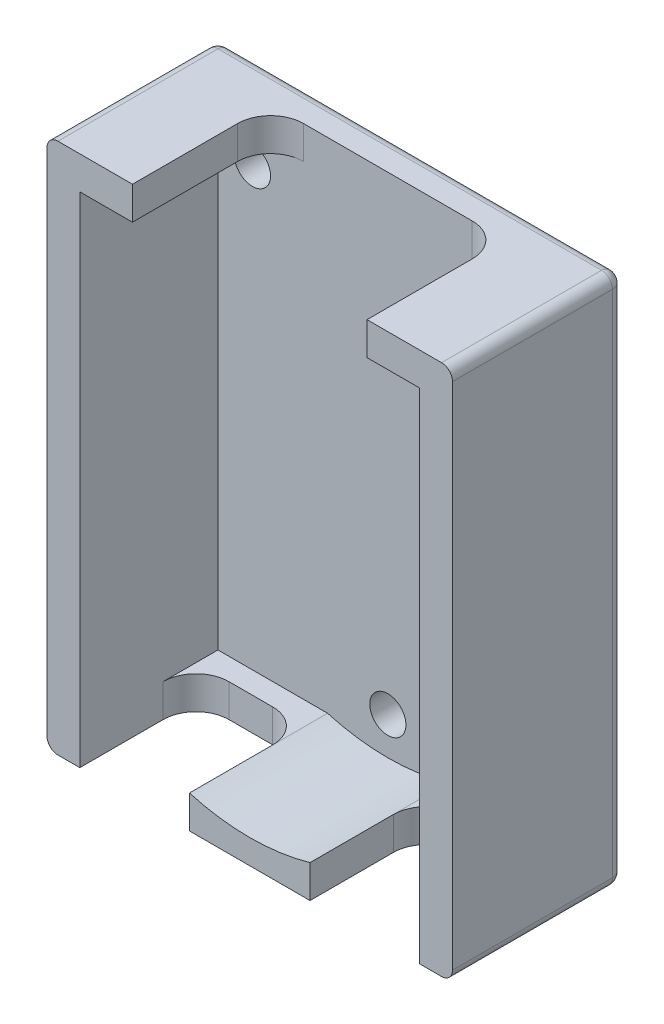
SolidWorks part; units mm, degrees
ref_plane "Front Plane" through (0, 0, 0) normal (0, 0, 1) x (1, 0, 0)
ref_plane "Top Plane" through (0, 0, 0) normal (0, 1, 0) x (1, 0, 0)
ref_plane "Right Plane" through (0, 0, 0) normal (1, 0, 0) x (0, 0, -1)
ref_plane "Plane1" through (0, 0, 0) normal (-0.7071, 0.7071, 0) x (0.7071, 0.7071, 0)
ref_plane "Plane2" through (0, 0, 0) normal (0.7071, 0.7071, 0) x (0.7071, -0.7071, 0)
sketch "Sketch1" plane through (0, 0, 0) normal (0, 0, 1) x (1, 0, 0)
  line L1 (-15.5, -21.25) -> (15.5, -21.25)
  line L2 (-15.5, -21.25) -> (-15.5, 21.25)
  line L3 (-15.5, 21.25) -> (15.5, 21.25)
  line L4 (15.5, -21.25) -> (15.5, 21.25)
  line L5 (-15.5, -21.25) -> (15.5, 21.25) construction
  line L6 (-15.5, 21.25) -> (15.5, -21.25) construction
  point P0 (0, 0)
  dimension "D1" = 31
  dimension "D2" = 42.5
extrude "Boss-Extrude1" add sketch "Sketch1" along normal blind 3
sketch "Sketch2" plane through (0, 0, 0) normal (0, 0, 1) x (1, 0, 0)
  line L0 (-18.5, -24.25) -> (-18.5, 24.25)
  line L1 (-15.5, -21.25) -> (15.5, -21.25)
  line L2 (-15.5, -21.25) -> (-15.5, 21.25)
  line L3 (-15.5, 21.25) -> (15.5, 21.25)
  line L4 (15.5, -21.25) -> (15.5, 21.25)
  line L5 (-15.5, -21.25) -> (15.5, 21.25) construction
  line L6 (-15.5, 21.25) -> (15.5, -21.25) construction
  line L7 (-18.5, 24.25) -> (18.5, 24.25)
  line L8 (18.5, -24.25) -> (18.5, 24.25)
  line L9 (-18.5, -24.25) -> (18.5, -24.25)
  line L10 (15.5, -21.25) -> (15.5, 21.25) construction
  line L11 (-15.5, -21.25) -> (15.5, -21.25) construction
  point P0 (0, 0)
  dimension "D1" = 3
extrude "Boss-Extrude2" add sketch "Sketch2" along normal blind 15.6
sketch "Sketch3" plane through (0, 0, 0) normal (0, 0, -1) x (-1, 0, 0)
  circle A0 centre (12.35, 18.6) radius 1.65
  circle A1 centre (0, -18.6) radius 1.65
  dimension "D1" = 3.3
  dimension "D2" = 12.35
  dimension "D3" = 18.6
  dimension "D4" = 18.6
extrude "Cut-Extrude1" cut sketch "Sketch3" against normal up to next
mirror "Mirror1" about plane through (0, 0, 0) normal (1, 0, 0) of "Cut-Extrude1"
sketch "Sketch4" plane through (0, 24.25, 0) normal (0, 1, 0) x (1, 0, 0)
  line L0 (18.5, -15.6) -> (-18.5, -15.6) construction
  line L1 (-10.7, -15.6) -> (10.7, -15.6)
  line L2 (-10.7, -15.6) -> (-10.7, -3)
  line L3 (-10.7, -3) -> (10.7, -3)
  line L4 (10.7, -15.6) -> (10.7, -3)
  line L5 (-10.7, -15.6) -> (10.7, -3) construction
  line L6 (-10.7, -3) -> (10.7, -15.6) construction
  line L8 (18.5, 0) -> (-18.5, 0) construction
  point P0 (0, -9.3)
  dimension "D1" = 3
extrude "Cut-Extrude2" cut sketch "Sketch4" against normal up to next
sketch "Sketch5" plane through (0, -24.25, 0) normal (0, -1, 0) x (1, 0, 0)
  line L0 (-18.5, 15.6) -> (18.5, 15.6) construction
  line L1 (15.5, 15.6) -> (5.5, 15.6)
  line L2 (15.5, 15.6) -> (15.5, 5)
  line L3 (15.5, 5) -> (5.5, 5)
  line L4 (5.5, 15.6) -> (5.5, 5)
  line L5 (15.5, 15.6) -> (5.5, 5) construction
  line L6 (15.5, 5) -> (5.5, 15.6) construction
  line L7 (-18.5, 0) -> (18.5, 0) construction
  line L8 (18.5, 15.6) -> (18.5, 0) construction
  line L9 (0, -1.65) -> (0, 1.65) construction
  point P0 (10.5, 10.3)
  dimension "D1" = 5
  dimension "D2" = 3
  dimension "D3" = 5.5
extrude "Cut-Extrude3" cut sketch "Sketch5" against normal up to next
mirror "Mirror2" about plane through (0, 0, 0) normal (1, 0, 0) of "Cut-Extrude3"
sketch "Sketch6" plane through (0, 0, 15.6) normal (0, 0, 1) x (1, 0, 0)
  line L0 (5.5, -21.25) -> (-5.5, -21.25)
  arc A0 (5.5, -21.25) -> (-5.5, -21.25) centre (0, -2.0211) cw
  dimension "D1" = 20
extrude "Cut-Extrude5" cut sketch "Sketch6" against normal up to surface (12.6 mm away) up to face at (10.7, 18.6, 3)
fillet "Fillet4" radius 1 8 edges at (-18.5, 24.25, 7.8) (-18.5, -24.25, 7.8) (18.5, 24.25, 7.8) (18.5, -24.25, 7.8) (0, 24.25, 0) (-18.5, 0, 0) (0, -24.25, 0) (18.5, 0, 0)
fillet "Fillet1" radius 3 6 edges at (-15.5, -22.75, 5) (-5.5, -22.75, 5) (5.5, -22.75, 5) (15.5, -22.75, 5) (-10.7, 22.75, 3) (10.7, 22.75, 3)
